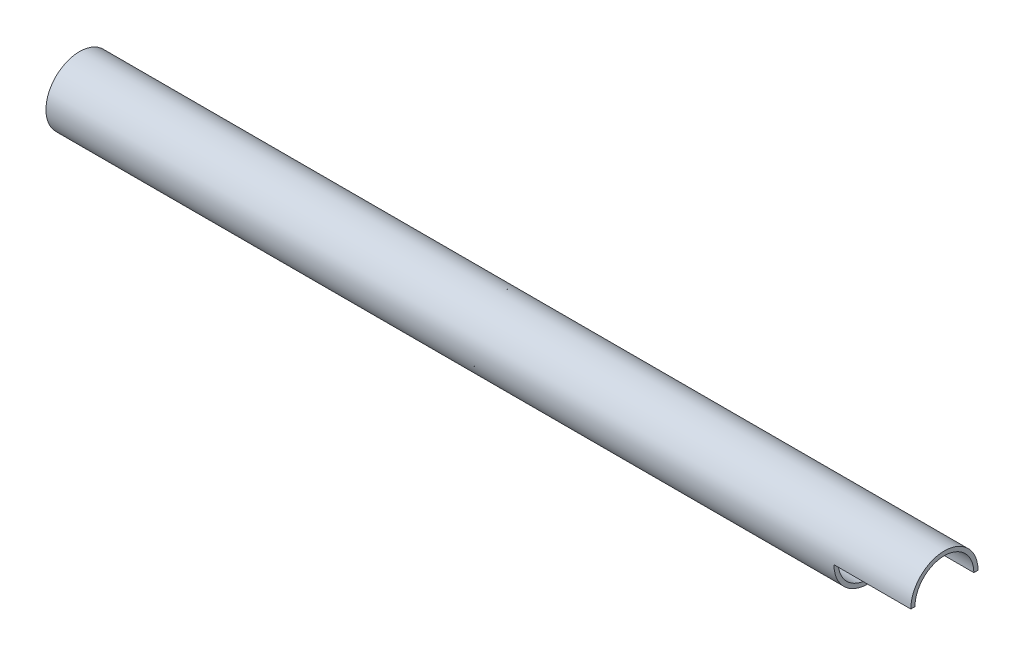
SolidWorks part; units mm, degrees
ref_plane "Front" through (0, 0, 0) normal (0, 0, 1) x (1, 0, 0)
ref_plane "Top" through (0, 0, 0) normal (0, 1, 0) x (1, 0, 0)
ref_plane "Right" through (0, 0, 0) normal (1, 0, 0) x (0, 0, -1)
sketch "Croquis1" plane through (0, 0, 0) normal (1, 0, 0) x (0, 0, -1)
  circle A1 centre (0, 0) radius 44.45
  circle A2 centre (0, 0) radius 38.95
  dimension "D1" = 88.9
  dimension "D2" = 5.5
extrude "Saliente-Extruir1" add sketch "Croquis1" along normal blind 1144
sketch "Croquis2" plane through (1144, 0, 0) normal (1, 0, 0) x (0, 0, -1)
  line L0 (-48.1402, -30.8) -> (48.1402, -30.8)
  arc A2 (-48.1402, -30.8) -> (48.1402, -30.8) centre (0, 0) ccw
  arc A3 (-40.8373, -30.8) -> (40.8373, -30.8) centre (0, 0) ccw
sketch "Croquis3" plane through (1144, 0, 0) normal (1, 0, 0) x (0, 0, -1)
  line L0 (-44.45, 0) -> (-38.95, 0)
  line L1 (38.95, 0) -> (44.45, 0)
  arc A2 (-44.45, 0) -> (44.45, 0) centre (0, 0) ccw
  arc A3 (-38.95, 0) -> (38.95, 0) centre (0, 0) ccw
  circle M1 centre (0, 0) radius 44.45
  circle M2 centre (0, 0) radius 38.95
extrude "Cortar-Extruir1" cut sketch "Croquis3" against normal blind 101.6 contours L1 L0 M2 M1
